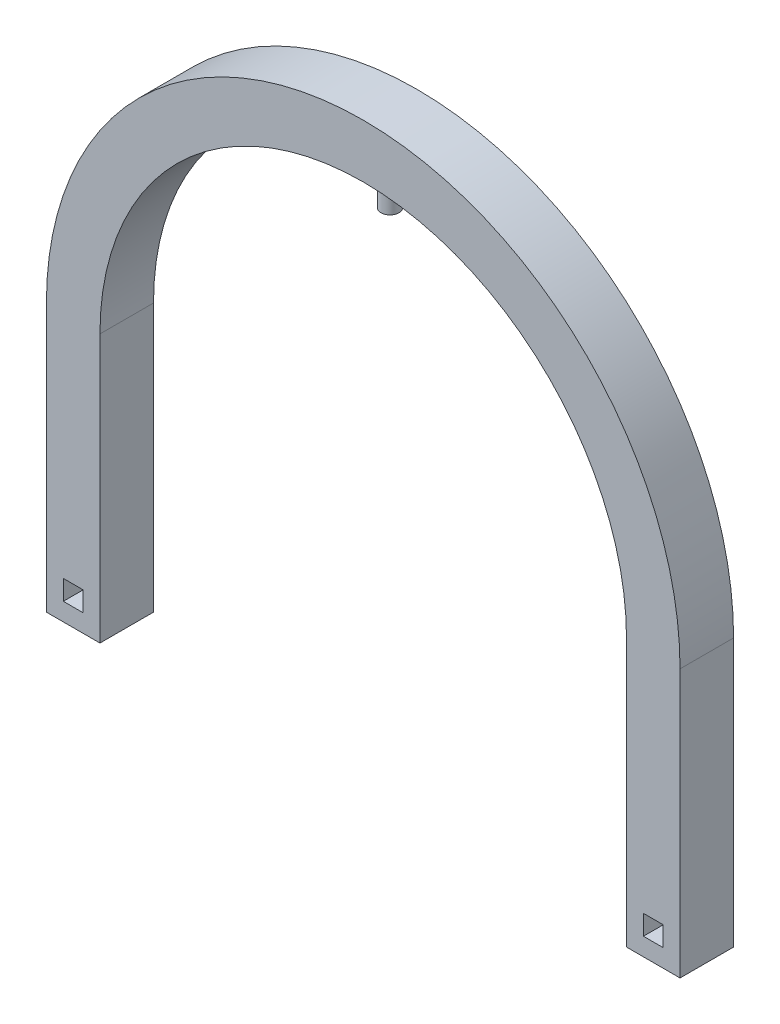
SolidWorks part; units mm, degrees
ref_plane "Front Plane" through (0, 0, 0) normal (0, 0, 1) x (1, 0, 0)
ref_plane "Top Plane" through (0, 0, 0) normal (0, 1, 0) x (1, 0, 0)
ref_plane "Right Plane" through (0, 0, 0) normal (1, 0, 0) x (0, 0, -1)
sketch "Sketch1" plane through (0, 0, 0) normal (0, 1, 0) x (1, 0, 0)
  line L0 (-55, 0) -> (55, 0) construction
  line L1 (-38.1, 38.1) -> (38.1, 38.1)
  line L2 (-38.1, 38.1) -> (-38.1, -38.1)
  line L3 (-38.1, -38.1) -> (38.1, -38.1)
  line L4 (38.1, 38.1) -> (38.1, -38.1)
  line L5 (-38.1, 38.1) -> (38.1, -38.1) construction
  line L6 (-38.1, -38.1) -> (38.1, 38.1) construction
  line L7 (-863.6, 38.1) -> (-787.4, 38.1)
  line L8 (-863.6, 38.1) -> (-863.6, -38.1)
  line L9 (-863.6, -38.1) -> (-787.4, -38.1)
  line L10 (-787.4, 38.1) -> (-787.4, -38.1)
  line L11 (-863.6, 38.1) -> (-787.4, -38.1) construction
  line L12 (-863.6, -38.1) -> (-787.4, 38.1) construction
  point P0 (0, 0)
  point P6 (-825.5, 0)
  dimension "D1" = 749.3
  dimension "D2" = 76.2
extrude "Boss-Extrude1" add sketch "Sketch1" along normal blind 381
sketch "Sketch3" plane through (0, 0, 0) normal (0, 0, 1) x (1, 0, 0)
  line L0 (0, -55) -> (0, 55) construction
  line L1 (-14.0236, 53.645) -> (14.0236, 53.645)
  line L2 (-14.0236, 53.645) -> (-14.0236, 25.4)
  line L3 (-14.0236, 25.4) -> (14.0236, 25.4)
  line L4 (14.0236, 53.645) -> (14.0236, 25.4)
  line L5 (-14.0236, 53.645) -> (14.0236, 25.4) construction
  line L6 (-14.0236, 25.4) -> (14.0236, 53.645) construction
  line L7 (-787.4, 381) -> (-38.1, 381) construction
  line L8 (55, 0) -> (-55, 0) construction
  line L9 (-412.75, 789.7688) -> (-412.75, -27.7688) construction
  line L10 (-811.4764, 25.4) -> (-839.5236, 53.645) construction
  line L11 (-811.4764, 53.645) -> (-839.5236, 25.4) construction
  line L12 (-839.5236, 53.645) -> (-839.5236, 25.4)
  line L13 (-811.4764, 25.4) -> (-839.5236, 25.4)
  line L14 (-811.4764, 53.645) -> (-811.4764, 25.4)
  line L15 (-811.4764, 53.645) -> (-839.5236, 53.645)
  point P0 (0, 39.5225)
  point P16 (-412.75, 381)
  point P20 (-825.5, 39.5225)
  dimension "D1" = 25.4
extrude "Cut-Extrude1" cut sketch "Sketch3" against normal through all both and the other way through all contours L14 L15 L12 L13 | L4 L1 L2 L3
sketch "Sketch4" plane through (0, 0, 0) normal (0, 0, 1) x (1, 0, 0)
  line L0 (-38.1, 381) -> (-787.4, 381) construction
  line L1 (-863.6, 381) -> (-787.4, 381)
  line L2 (-38.1, 381) -> (38.1, 381)
  arc A0 (-38.1, 381) -> (-787.4, 381) centre (-412.75, 381) ccw
  arc A1 (38.1, 381) -> (-863.6, 381) centre (-412.75, 381) ccw
extrude "Boss-Extrude2" add sketch "Sketch4" along normal through all and the other way through all
ref_plane "Plane1" through (0, 755.65, 0) normal (0, 1, 0) x (1, 0, 0)
sketch "Sketch5" plane through (0, 755.65, 0) normal (0, 1, 0) x (1, 0, 0)
  line L0 (-457.5175, 0) -> (457.5175, 0) construction
  circle A0 centre (-412.75, 0) radius 12.7
  dimension "D1" = 25.4
extrude "Boss-Extrude3" add sketch "Sketch5" against normal blind 50.8
